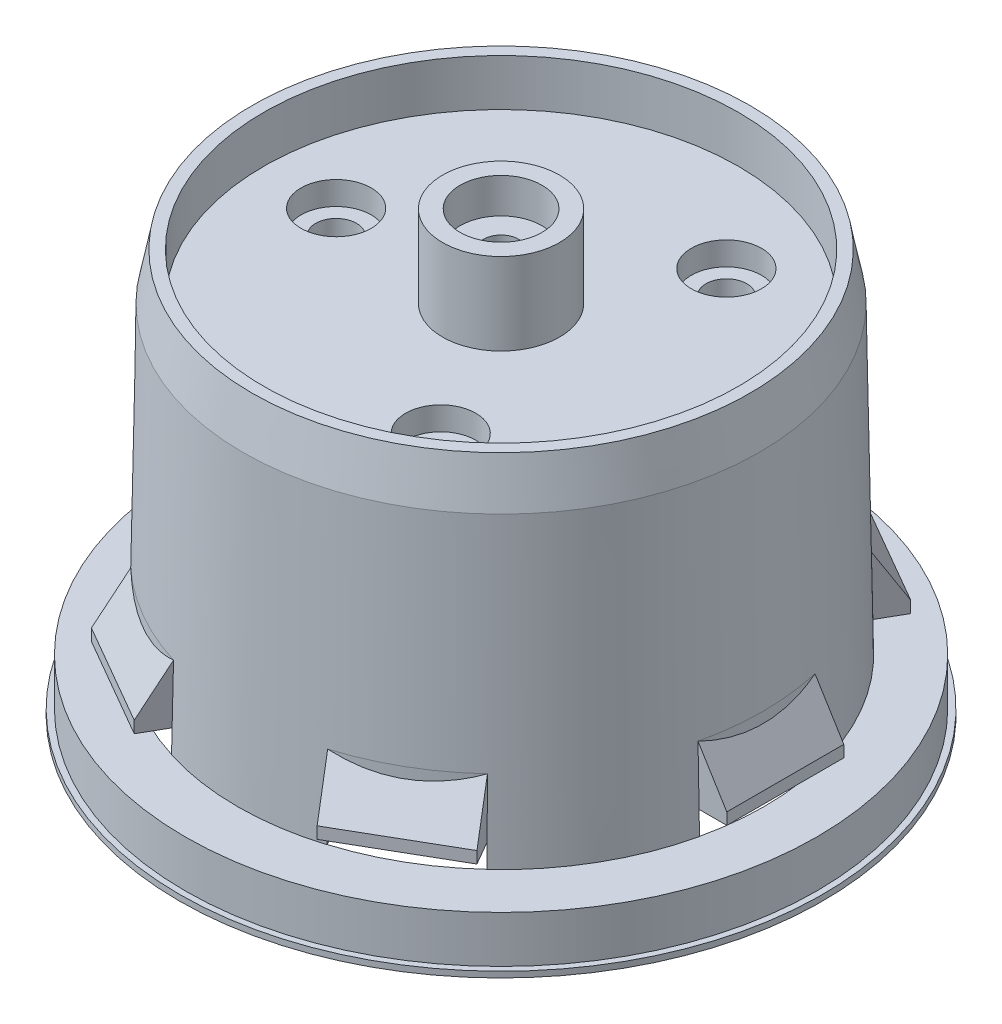
SolidWorks part; units mm, degrees
material "ABS PC"
ref_plane "Piano frontale" through (0, 0, 0) normal (0, 0, 1) x (1, 0, 0)
ref_plane "Piano superiore" through (0, 0, 0) normal (0, 1, 0) x (1, 0, 0)
ref_plane "Piano destro" through (0, 0, 0) normal (1, 0, 0) x (0, 0, -1)
sketch "Schizzo1" plane through (0, 0, 0) normal (0, 1, 0) x (1, 0, 0)
  circle A0 centre (0, 0) radius 22
  dimension "D1" = 44
extrude "Estrusione-Estrusione1" add sketch "Schizzo1" along normal blind 30
draft "Sformo1" type of draft neutral plane draft angle 1 faces to draft 1 face at (0, 30, 22) neutral plane through (0, 30, 0) neutral plane normal (0, 1, 0) parameters "D1"=1
chamfer "Smusso1" distance 4 angle 10 1 edges at (0, 30, 22)
sketch "Schizzo2" plane through (0, 30, 0) normal (0, 1, 0) x (1, 0, 0)
  circle A0 centre (0, 0) radius 20.2924
  circle A1 centre (0, 0) radius 21.2924 construction
  dimension "D1" = 1
extrude "Taglio-Estrusione1" cut sketch "Schizzo2" against normal blind 4
shell "Svuota1" thickness 3
sketch "Schizzo4" plane through (0, 26, 0) normal (0, 1, 0) x (1, 0, 0)
  line L0 (-17.5737, 10.1462) -> (17.5737, -10.1462) construction
  line L1 (17.5737, 10.1462) -> (-17.5737, -10.1462) construction
  line L2 (0, -20.2924) -> (0, 20.2924) construction
  line L3 (0, 0) -> (10.1462, 17.5737) construction
  circle A0 centre (0, 0) radius 20.2924 construction
  circle A1 centre (0, 0) radius 20.2924 construction
  circle A3 centre (7.05, 12.211) radius 3
  point P7 (0, 0)
  point P13 (0, 0)
  point P17 (0, 0)
  dimension "D5" = 6
  dimension "D1" = 60
  dimension "D2" = 60
  dimension "D3" = 30
  dimension "D4" = 14.1
extrude "Taglio-Estrusione2" cut sketch "Schizzo4" against normal blind 2
sketch "Schizzo5" plane through (0, 24, 0) normal (0, 1, 0) x (1, 0, 0)
  circle A0 centre (7.05, 12.211) radius 1.75
  dimension "D1" = 3.5
extrude "Taglio-Estrusione3" cut sketch "Schizzo5" against normal through all
pattern_circular "RipetizioneCircolare1" count 3 over 360 about axis through (0, 0, 0) along (0, 1, 0) of "Taglio-Estrusione3", "Taglio-Estrusione2"
sketch "Schizzo3" plane through (0, 26, 0) normal (0, 1, 0) x (1, 0, 0)
  circle A0 centre (0, 0) radius 5
  dimension "D1" = 10
extrude "Estrusione-Estrusione2" add sketch "Schizzo3" along normal blind 7
sketch "Schizzo6" plane through (0, 33, 0) normal (0, 1, 0) x (1, 0, 0)
  circle A0 centre (0, 0) radius 3.5
  dimension "D1" = 7
extrude "Taglio-Estrusione5" cut sketch "Schizzo6" against normal blind 3
sketch "Schizzo8" plane through (0, 23, 0) normal (0, -1, 0) x (1, 0, 0)
  line L0 (-17.5737, -10.1462) -> (17.5737, 10.1462) construction
  line L1 (0, 20.2924) -> (0, -20.2924) construction
  line L2 (17.5737, -10.1462) -> (-17.5737, 10.1462) construction
  line L3 (-17.5737, -10.1462) -> (17.5737, 10.1462)
  line L4 (0, 20.2924) -> (0, -20.2924)
  line L5 (17.5737, -10.1462) -> (-17.5737, 10.1462)
extrude "Estrusione-Sottile1" add sketch "Schizzo8" along normal blind 8 thin thin type mid plane wall 1
sketch "Schizzo7" plane through (0, 30, 0) normal (0, 1, 0) x (1, 0, 0)
  circle A0 centre (0, 0) radius 2.5
  circle A1 centre (0, 0) radius 1.5
  dimension "D1" = 5
  dimension "D2" = 3
extrude "Estrusione-Estrusione5" add sketch "Schizzo7" against normal offset from surface (17 mm away) 2 up to face at (0, 15, 0) offset beyond the face yes
sketch "Schizzo10" plane through (0, 30, 0) normal (0, 1, 0) x (1, 0, 0)
  circle A0 centre (0, 0) radius 1.5 construction
  circle A1 centre (0, 0) radius 1.5
extrude "Taglio-Estrusione7" cut sketch "Schizzo10" against normal through all
sketch "Schizzo11" plane through (0, 15, 0) normal (0, -1, 0) x (1, 0, 0)
  line L1 (-0.5, -2.4495) -> (-0.5, -19.2549) construction
  line L2 (0.5, -2.4495) -> (0.5, -19.1152) construction
  line L4 (0.5, -2.4495) -> (0.5, -19.2549) construction
  line L5 (-0.5, -10.8522) -> (0.5, -10.8522) construction
  line L6 (-0.5, -2.4495) -> (-0.5, -19.1152) construction
  circle A0 centre (0, -10.8522) radius 0.75
  point P2 (0.5, -10.8522)
  point P4 (-0.5, -10.8522)
  dimension "D1" = 1.5
extrude "Estrusione-Estrusione6" add sketch "Schizzo11" against normal up to surface (8 mm away) up to face at (-5.0997, 23, -8.8329)
pattern_circular "RipetizioneCircolare2" count 6 over 360 about axis through (0, 0, 0) along (0, 1, 0) of "Estrusione-Estrusione6"
sketch "Schizzo12" plane through (0, 23, 0) normal (0, -1, 0) x (1, 0, 0)
  circle A0 centre (7.05, -12.211) radius 3.5
  circle A1 centre (7.05, -12.211) radius 1.75 construction
  circle A2 centre (7.05, -12.211) radius 1.75
  dimension "D1" = 7
extrude "Estrusione-Estrusione7" add sketch "Schizzo12" along normal blind 5
sketch "Schizzo13" plane through (0, 18, 0) normal (0, -1, 0) x (1, 0, 0)
  circle A0 centre (7.05, -12.211) radius 3
  circle A1 centre (7.05, -12.211) radius 3.5 construction
  dimension "D1" = 0.5
extrude "Taglio-Estrusione8" cut sketch "Schizzo13" against normal blind 1.5
pattern_circular "RipetizioneCircolare3" count 3 over 360 about axis through (0, 0, 0) along (0, 1, 0) of "Taglio-Estrusione8", "Estrusione-Estrusione7"
sketch "Schizzo14" plane through (0, 0, 0) normal (0, -1, 0) x (1, 0, 0)
  circle A0 centre (0, 0) radius 27
  circle A1 centre (0, 0) radius 22.5
  dimension "D1" = 54
  dimension "D2" = 45
extrude "Estrusione-Estrusione8" add sketch "Schizzo14" along normal blind 4
sketch "Schizzo16" plane through (0, -4, 0) normal (0, -1, 0) x (1, 0, 0)
  circle A0 centre (0, 0) radius 27.5
  circle A1 centre (0, 0) radius 26.5
  dimension "D1" = 53
  dimension "D2" = 55
extrude "Estrusione-Estrusione9" add sketch "Schizzo16" along normal blind 0.5
ref_plane "Piano1" through (11.1484, 0, -19.3095) normal (0.5, 0, -0.866) x (0, 1, 0)
sketch "Schizzo17" plane through (11.1484, 0, -19.3095) normal (0.5, 0, -0.866) x (0, 1, 0)
  line L0 (0, -27) -> (0, 27) construction
  line L1 (0, -5) -> (2, -5)
  line L2 (0, -5) -> (0, 5)
  line L3 (0, 5) -> (2, 5)
  line L4 (2, -5) -> (2, 5)
  dimension "D1" = 10
  dimension "D2" = 2
extrude "Taglio-Estrusione9" cut sketch "Schizzo17" against normal mid plane 8
sketch "Schizzo18" plane through (11.1484, 0, -19.3095) normal (0.5, 0, -0.866) x (0, 1, 0)
  line L0 (2, -5) -> (0, -5) construction
  line L1 (2, 5) -> (7, 5)
  line L2 (2, 5) -> (2, -5)
  line L3 (2, -5) -> (7, -5)
  line L4 (7, 5) -> (7, -5)
  dimension "D1" = 5
extrude "Estrusione-Estrusione10" add sketch "Schizzo18" along normal mid plane 4
sketch "Schizzo19" plane through (-4.3301, 0, -2.5) normal (-0.866, 0, -0.5) x (-0.5, 0, 0.866)
  line L0 (-21.8363, 7) -> (-24.2967, 3)
  line L1 (-24.2967, 2) -> (-24.2967, 7) construction
  line L2 (-24.2967, 3) -> (-24.2967, 7)
  line L3 (-24.2967, 7) -> (-21.8363, 7)
  line L4 (-24.2967, 2) -> (-21.9259, 2) construction
  line L5 (-24.2967, 7) -> (-21.8363, 7) construction
  line L6 (-21.9259, 2) -> (-21.8363, 7) construction
  dimension "D1" = 1
extrude "Taglio-Estrusione10" cut sketch "Schizzo19" against normal blind 10
sketch "Schizzo20" plane through (0, 7, 0) normal (0, -1, 0) x (1, 0, 0)
  line L1 (15.2483, -16.4108) -> (6.588, -21.4108)
  line L2 (15.2483, -16.4108) -> (6.588, -21.4108)
  arc A1 (6.588, -21.4108) -> (15.2483, -16.4108) centre (0, 0) ccw
  arc A2 (6.588, -21.4108) -> (15.2483, -16.4108) centre (0, 0) ccw
  dimension "D1" = 0
extrude "Estrusione-Estrusione11" add sketch "Schizzo20" along normal blind 1
pattern_circular "RipetizioneCircolare11" count 6 over 360 about axis through (0, 0, 0) along (0, 1, 0) of "Estrusione-Estrusione10", "Taglio-Estrusione9", "Taglio-Estrusione10", "Estrusione-Estrusione11"
move or copy body "Corpo-Sposta/copia1" [suppressed]
move or copy body "Corpo-Sposta/copia2"
